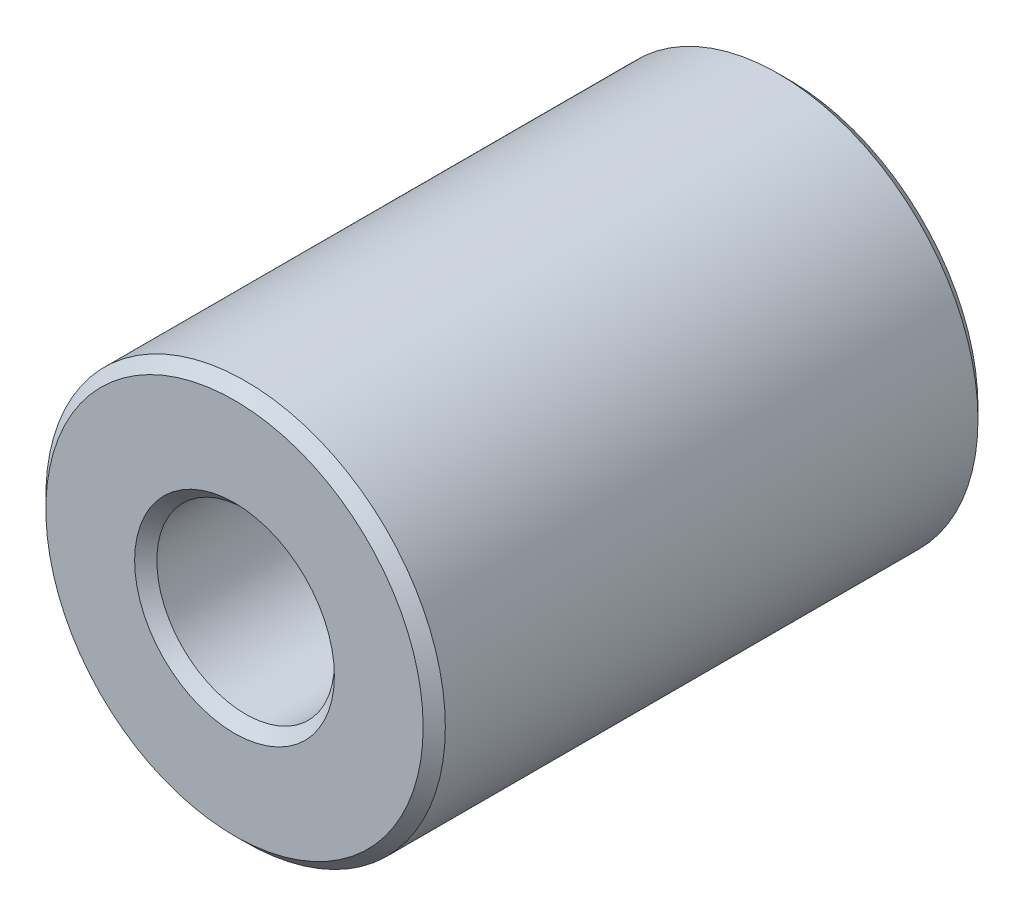
SolidWorks part; units mm, degrees
ref_plane "Płaszczyzna przednia" through (0, 0, 0) normal (0, 0, 1) x (1, 0, 0)
ref_plane "Płaszczyzna górna" through (0, 0, 0) normal (0, 1, 0) x (1, 0, 0)
ref_plane "Płaszczyzna prawa" through (0, 0, 0) normal (1, 0, 0) x (0, 0, -1)
sketch "Szkic1" plane through (0, 0, 0) normal (0, 0, 1) x (1, 0, 0)
  circle A0 centre (0, 0) radius 9
extrude "Dodanie-wyciągnięcie1" add sketch "Szkic1" along normal blind 25
sketch "Szkic2" plane through (0, 0, 25) normal (0, 0, 1) x (1, 0, 0)
  circle A0 centre (0, 0) radius 4
extrude "Wytnij-wyciągnięcie1" cut sketch "Szkic2" against normal blind 10
sketch "Szkic3" plane through (0, 0, 0) normal (0, 0, -1) x (-1, 0, 0)
  circle A0 centre (0, 0) radius 2.5
extrude "Wytnij-wyciągnięcie2" cut sketch "Szkic3" against normal blind 10
chamfer "Sfazowanie1" distance 0.5 angle 45 4 edges at (4, 0, 25) (9, 0, 25) (9, 0, 0) (-2.5, 0, 0)
